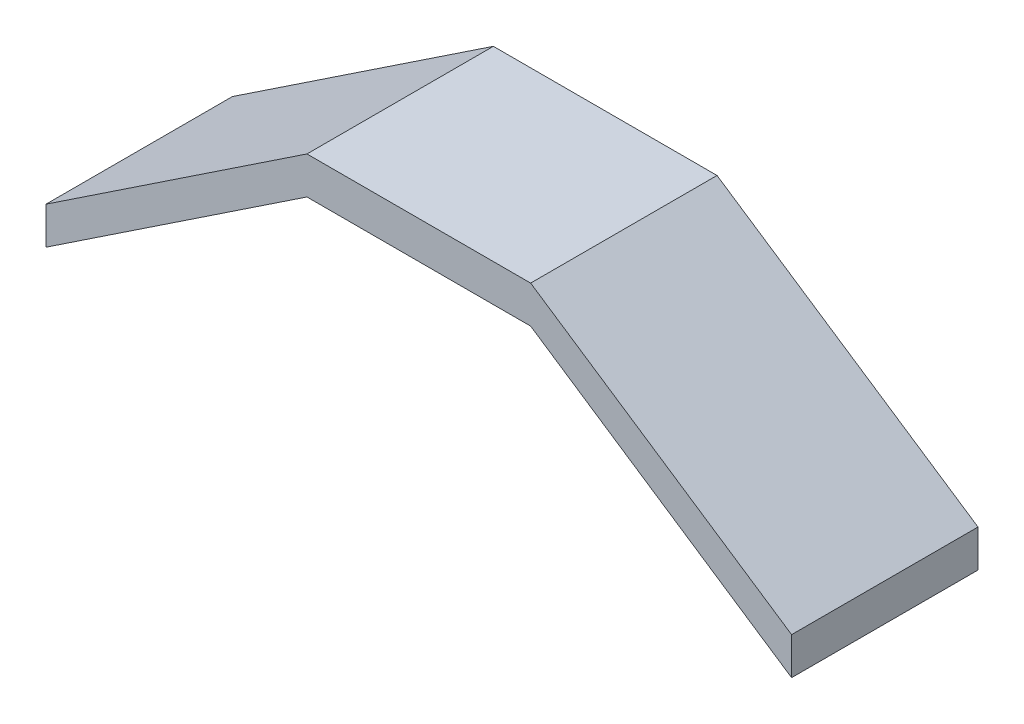
SolidWorks part; units mm, degrees
ref_plane "Front Plane" through (0, 0, 0) normal (0, 0, 1) x (1, 0, 0)
ref_plane "Top Plane" through (0, 0, 0) normal (0, 1, 0) x (1, 0, 0)
ref_plane "Right Plane" through (0, 0, 0) normal (1, 0, 0) x (0, 0, -1)
sketch "Sketch1" plane through (0, 0, 0) normal (0, 0, 1) x (1, 0, 0)
  line L1 (-50, -25) -> (50, -25)
  line L2 (-50, -25) -> (-50, 25)
  line L3 (-50, 25) -> (50, 25)
  line L4 (50, -25) -> (50, 25)
  line L5 (-50, -25) -> (50, 25) construction
  line L6 (-50, 25) -> (50, -25) construction
  point P0 (0, 0)
  dimension "D1" = 100
  dimension "D2" = 50
extrude "Boss-Extrude1" add sketch "Sketch1" along normal blind 5
sketch "Sketch2" plane through (0, 0, 0) normal (0, 0, -1) x (-1, 0, 0)
  line L0 (-14.9969, 25.0021) -> (-53.7386, -0.8257) construction
  line L1 (-14.9969, 25.0021) -> (-50, 1.6667)
  line L2 (-50, -25) -> (-50, 25) construction
  line L3 (-50, 1.6667) -> (-50, 25)
  line L4 (-50, 25) -> (50, 25) construction
  line L5 (-50, 25) -> (-15, 25)
  line L6 (53.7386, -0.8257) -> (14.9969, 25.0021) construction
  line L7 (50, 1.6667) -> (14.9969, 25.0021)
  line L8 (50, 25) -> (50, -25) construction
  line L9 (50, 25) -> (50, 1.6667)
  line L10 (15, 25) -> (50, 25)
  line M1 (-50, 25) -> (-50, -25)
  line M3 (50, -25) -> (50, 25)
  line M4 (50, 25) -> (-50, 25)
extrude "Cut-Extrude1" cut sketch "Sketch2" against normal through all contours L1 M4 M1 | L7 M3 M4
sketch "Sketch3" plane through (0, 0, 5) normal (0, 0, 1) x (1, 0, 0)
  line L0 (-50, -3.3333) -> (-15, 20)
  line L1 (-50, 1.6667) -> (-50, -25) construction
  line L2 (-15, 20) -> (15, 20)
  line L3 (15, 20) -> (50, -3.3333)
  line L4 (50, -25) -> (50, 1.6667) construction
  line L5 (15, 25) -> (50, 1.6667) construction
  line L6 (-50, 1.6667) -> (-15, 25) construction
  line L8 (15, 25) -> (-15, 25) construction
  line L9 (-50, -3.3333) -> (-50, -25)
  line L10 (-50, -25) -> (50, -25)
  line L11 (50, -25) -> (50, -3.3333)
  dimension "D1" = 5
  dimension "D2" = 5
  dimension "D3" = 5
extrude "Cut-Extrude2" cut sketch "Sketch3" against normal through all
sketch "Sketch4" plane through (0, 0, 5) normal (0, 0, 1) x (1, 0, 0)
  line L8 (-50, 1.6667) -> (-50, -3.3333)
  line L9 (-50, -3.3333) -> (-15, 20)
  line L10 (-15, 20) -> (15, 20)
  line L11 (15, 20) -> (50, -3.3333)
  line L12 (50, -3.3333) -> (50, 1.6667)
  line L13 (50, 1.6667) -> (15, 25)
  line L14 (15, 25) -> (-15, 25)
  line L15 (-15, 25) -> (-50, 1.6667)
  line L16 (-50, 1.6667) -> (-50, -3.3333)
  line L17 (-50, -3.3333) -> (-15, 20)
  line L18 (-15, 20) -> (15, 20)
  line L19 (15, 20) -> (50, -3.3333)
  line L20 (50, -3.3333) -> (50, 1.6667)
  line L21 (50, 1.6667) -> (15, 25)
  line L22 (15, 25) -> (-15, 25)
  line L23 (-15, 25) -> (-50, 1.6667)
  dimension "D1" = 0
extrude "Boss-Extrude2" add sketch "Sketch4" along normal blind 20
